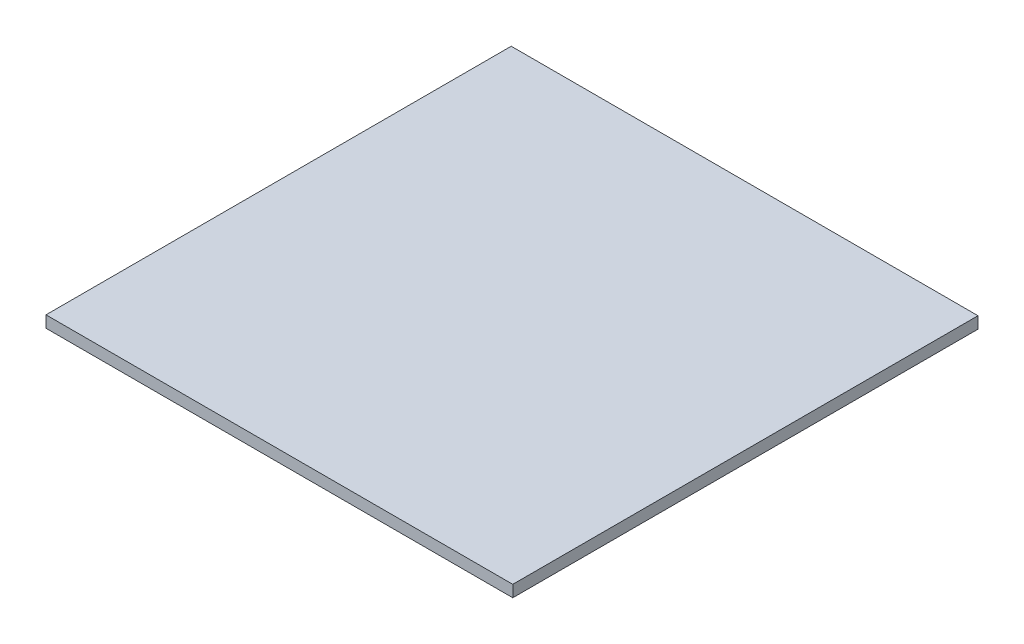
SolidWorks part; units mm, degrees
ref_plane "Front Plane" through (0, 0, 0) normal (0, 0, 1) x (1, 0, 0)
ref_plane "Top Plane" through (0, 0, 0) normal (0, 1, 0) x (1, 0, 0)
ref_plane "Right Plane" through (0, 0, 0) normal (1, 0, 0) x (0, 0, -1)
sketch "Sketch1" plane through (0, 0, 0) normal (0, 1, 0) x (1, 0, 0)
  line L1 (-600, -598) -> (600, -598)
  line L2 (-600, -598) -> (-600, 598)
  line L3 (-600, 598) -> (600, 598)
  line L4 (600, -598) -> (600, 598)
  line L5 (-600, -598) -> (600, 598) construction
  line L6 (-600, 598) -> (600, -598) construction
  point P0 (0, 0)
  dimension "D1" = 1196
  dimension "D2" = 1200
extrude "Boss-Extrude1" add sketch "Sketch1" along normal blind 30
